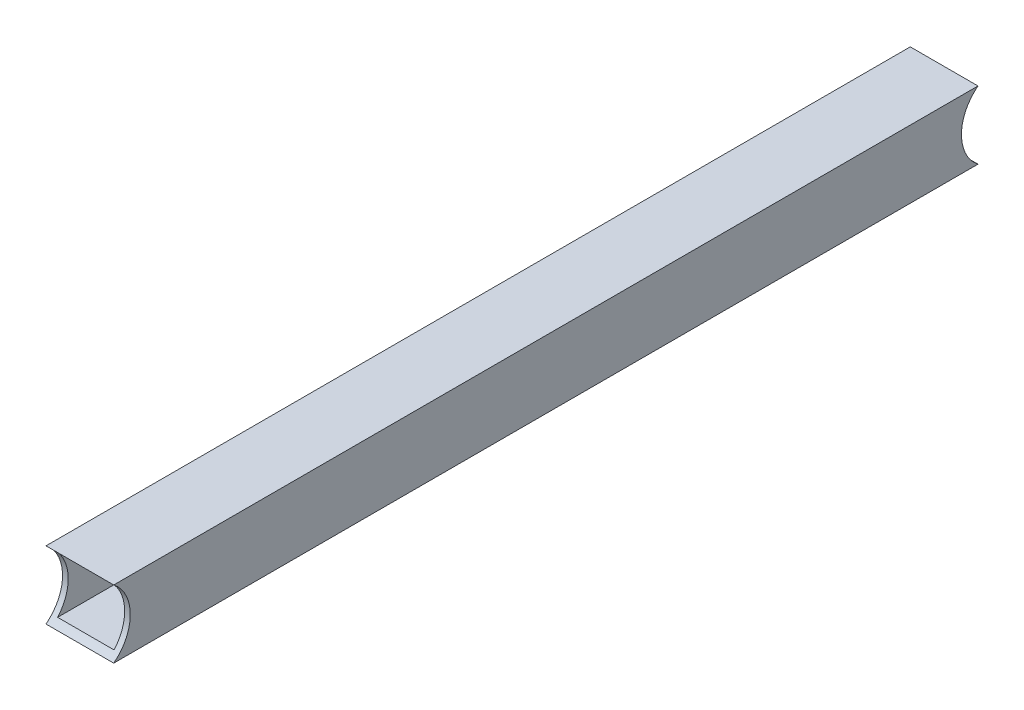
SolidWorks part; units mm, degrees
material "6063-T5"
ref_plane "Front Plane" through (0, 0, 0) normal (0, 0, 1) x (1, 0, 0)
ref_plane "Top Plane" through (0, 0, 0) normal (0, 1, 0) x (1, 0, 0)
ref_plane "Right Plane" through (0, 0, 0) normal (1, 0, 0) x (0, 0, -1)
sketch "Sketch1" plane through (0, 0, 0) normal (1, 0, 0) x (0, 0, -1)
  line L1 (0, 0) -> (515.7572, 0)
  line L2 (0, 0) -> (0, 38.1)
  line L3 (0, 38.1) -> (515.7572, 38.1)
  line L4 (515.7572, 0) -> (515.7572, 38.1)
  circle A0 centre (0, 19.05) radius 24.13
  circle A1 centre (515.7572, 19.05) radius 24.13
  dimension "D2" = 48.26
  dimension "D3" = 48.26
  dimension "D1" = 38.1
  dimension "D4" = 515.7572
extrude "Boss-Extrude1" add sketch "Sketch1" along normal blind 38.1 contours A1 L3 A0 L1
sketch "Sketch2" plane through (0, 0, 0) normal (0, 0, 1) x (1, 0, 0)
  line L0 (3.175, 34.925) -> (3.175, 3.175)
  line L1 (3.175, 3.175) -> (34.925, 3.175)
  line L2 (34.925, 3.175) -> (34.925, 34.925)
  line L3 (34.925, 34.925) -> (3.175, 34.925)
  line L4 (0, 38.1) -> (0, 0)
  line L5 (0, 0) -> (38.1, 0)
  line L6 (38.1, 0) -> (38.1, 38.1)
  line L7 (38.1, 38.1) -> (0, 38.1)
  line L8 (0, 38.1) -> (0, 0) construction
  line L9 (0, 0) -> (38.1, 0) construction
  line L10 (38.1, 0) -> (38.1, 38.1) construction
  line L11 (38.1, 38.1) -> (0, 38.1) construction
  dimension "D1" = 0
  dimension "D2" = 3.175
extrude "Cut-Extrude1" cut sketch "Sketch2" against normal through all
ref_plane "Plane1" through (0, 0, -14.8106) normal (0, 0, -1) x (-1, 0, 0)
ref_plane "Plane2" through (0, 0, -500.9465) normal (0, 0, -1) x (-1, 0, 0)
